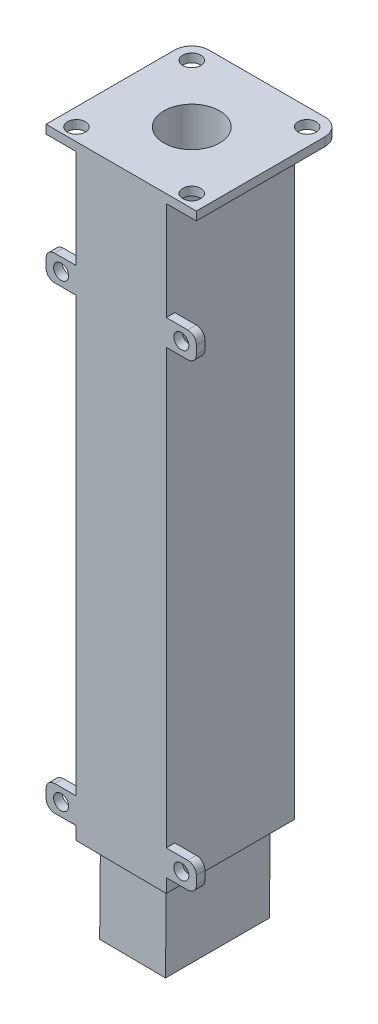
SolidWorks part; units mm, degrees
ref_plane "Plan de face" through (0, 0, 0) normal (0, 0, 1) x (1, 0, 0)
ref_plane "Plan de dessus" through (0, 0, 0) normal (0, 1, 0) x (1, 0, 0)
ref_plane "Plan de droite" through (0, 0, 0) normal (1, 0, 0) x (0, 0, -1)
sketch "Esquisse1" plane through (0, 0, 0) normal (0, 1, 0) x (1, 0, 0)
  line L0 (0, 0) -> (35, 0)
  line L1 (35, 0) -> (35, -35)
  line L2 (0, 0) -> (0, -35)
  line L3 (0, -35) -> (35, -35)
  dimension "D1" = 35
  dimension "D2" = 35
extrude "Boss.-Extru.1" add sketch "Esquisse1" along normal blind 2
sketch "Esquisse2" plane through (0, 2, 0) normal (0, 1, 0) x (1, 0, 0)
  line L0 (0, -33.935) -> (0, -35)
  line L1 (0, -33.935) -> (35, -33.935)
  line L6 (0, 0) -> (0, -35) construction
  line L7 (35, -35) -> (35, 0) construction
  line L8 (0, -35) -> (35, -35)
  line L9 (35, -35) -> (35, -33.935)
  circle A9 centre (30.935, -4.065) radius 1.75
  circle A10 centre (30.935, -30.935) radius 1.75
  circle A11 centre (4.065, -4.065) radius 1.75
  circle A12 centre (4.065, -30.935) radius 1.75
extrude "Enlèv. mat.-Extru.1" cut sketch "Esquisse2" against normal blind 2
sketch "Esquisse4" plane through (0, 2, 0) normal (0, 1, 0) x (1, 0, 0)
  line L0 (17.5, -33.935) -> (7, -33.935)
  line L1 (35, -33.935) -> (0, -33.935) construction
  line L2 (17.5, -33.935) -> (28, -33.935)
  line L3 (7, -4.065) -> (28, -4.065)
  line L4 (7, -33.935) -> (7, -4.065)
  line L5 (28, -4.065) -> (28, -33.935)
extrude "Boss.-Extru.2" add sketch "Esquisse4" along normal blind 280
sketch "Esquisse5" plane through (0, 0, 33.935) normal (0, 0, 1) x (1, 0, 0)
  line L0 (28, 251) -> (28, 257)
  line L1 (7, 282) -> (7, 2) construction
  line L2 (35, 251) -> (35, 257)
  line L3 (28, 282) -> (28, 2) construction
  line L4 (7, 31) -> (0, 31)
  line L5 (7, 25) -> (0, 25)
  line L6 (28, 25) -> (35, 25)
  line L7 (28, 282) -> (28, 257)
  line L8 (28, 257) -> (28, 25)
  line L10 (28, 251) -> (35, 251)
  line L11 (7, 251) -> (7, 257)
  line L12 (0, 31) -> (0, 25)
  line L13 (7, 31) -> (7, 25)
  line L14 (28, 31) -> (35, 31)
  line L15 (35, 31) -> (35, 25)
  line L16 (28, 31) -> (28, 25)
  line L17 (0, 251) -> (0, 257)
  line L18 (28, 257) -> (35, 257)
  line L19 (7, 257) -> (0, 257)
  line L20 (7, 251) -> (0, 251)
  circle A0 centre (3.5, 28) radius 1.75
  circle A1 centre (31.5, 28) radius 1.75
  circle A2 centre (31.5, 254) radius 1.75
  circle A3 centre (3.5, 254) radius 1.75
  line M4 (28, 2) -> (28, 282)
  line M6 (7, 282) -> (7, 2)
extrude "Boss.-Extru.3" add sketch "Esquisse5" against normal blind 2 contours L18 L10 L2 A2 M4 | L20 L19 L17 A3 M6 | L15 L14 L6 A1 M4 | L4 L12 L5 A0 M6
sketch "Esquisse6" plane through (0, 0, 33.935) normal (0, 0, 1) x (1, 0, 0)
  line L7 (0, 144) -> (0, 138)
  line L8 (0, 138) -> (7, 138)
  line L9 (7, 141) -> (7, 138)
  line L10 (7, 141) -> (7, 144)
  line L11 (0, 144) -> (7, 144)
  line L12 (0, 144) -> (0, 141)
  line L13 (0, 144) -> (7, 144)
  line L14 (28, 251) -> (28, 31) construction
  line L15 (28, 144) -> (28, 138)
  line L16 (28, 138) -> (35, 138)
  line L17 (35, 141) -> (35, 138)
  line L18 (35, 141) -> (35, 144)
  line L19 (28, 144) -> (35, 144)
  line L20 (28, 144) -> (28, 141)
  line L21 (0, 144) -> (0, 138)
  line L22 (0, 138) -> (7, 138)
  line L23 (7, 144) -> (7, 138)
  circle A1 centre (3.5, 141) radius 1.75
  circle A2 centre (31.5, 141) radius 1.75
  line M21 (28, 31) -> (28, 251)
  line M31 (7, 251) -> (7, 31)
extrude "Boss.-Extru.4" add sketch "Esquisse6" against normal blind 2 contours L11 L7 L8 A1 M31 | L19 L15 L16 L17 L18 A2 M21
sketch "Esquisse10" plane through (0, 282, 0) normal (0, 1, 0) x (1, 0, 0)
  line L0 (35, -33.935) -> (0, -33.935)
  line L1 (35, -33.935) -> (35, 0)
  line L2 (35, 0) -> (0, 0)
  line L3 (0, -33.935) -> (0, 0)
  circle A0 centre (30.935, -30.935) radius 1.75
  circle A1 centre (30.935, -4.065) radius 1.75
  circle A2 centre (4.065, -4.065) radius 1.75
  circle A3 centre (4.065, -30.935) radius 1.75
extrude "Boss.-Extru.5" add sketch "Esquisse10" against normal blind 2
sketch "Esquisse15" plane through (0, 282, 0) normal (0, 1, 0) x (1, 0, 0)
  circle A0 centre (17.5, -17.5) radius 6.5
  circle A1 centre (30.935, -4.065) radius 1.75
extrude "Enlèv. mat.-Extru.2" cut sketch "Esquisse15" against normal blind 373
fillet "Congé1" radius 2 12 edges at (35, 138, 32.935) (35, 144, 32.935) (35, 25, 32.935) (35, 31, 32.935) (0, 31, 32.935) (0, 25, 32.935) (0, 138, 32.935) (0, 144, 32.935) (0, 251, 32.935) (0, 257, 32.935) (35, 251, 32.935) (35, 257, 32.935)
fillet "Congé2" radius 4 4 edges at (0, 1, 0) (35, 1, 0) (0, 281, 0) (35, 281, 0)
sketch "Esquisse17" plane through (0, 0, 33.935) normal (0, 0, 1) x (1, 0, 0)
  line L0 (7, 144) -> (7, 138)
  line L1 (7, 138) -> (2, 138)
  line L2 (7, 144) -> (2, 144)
  line L3 (28, 144) -> (28, 138)
  line L4 (28, 138) -> (33, 138)
  line L5 (28, 144) -> (33, 144)
  line L6 (35, 142) -> (35, 140)
  line L7 (0, 142) -> (0, 140)
  line L8 (7, 150) -> (7, 144)
  line L9 (7, 144) -> (2, 144)
  line L10 (7, 150) -> (2, 150)
  line L11 (28, 150) -> (28, 144)
  line L12 (28, 144) -> (33, 144)
  line L13 (28, 150) -> (33, 150)
  line L14 (35, 148) -> (35, 146)
  line L15 (0, 148) -> (0, 146)
  line L16 (7, 138) -> (7, 132)
  line L17 (7, 132) -> (2, 132)
  line L18 (7, 138) -> (2, 138)
  line L19 (28, 138) -> (28, 132)
  line L20 (28, 132) -> (33, 132)
  line L21 (28, 138) -> (33, 138)
  line L22 (35, 136) -> (35, 134)
  line L23 (0, 136) -> (0, 134)
  arc A0 (0, 142) -> (2, 144) centre (2, 142) cw
  arc A2 (0, 140) -> (2, 138) centre (2, 140) ccw
  arc A3 (33, 144) -> (35, 142) centre (33, 142) cw
  arc A4 (35, 140) -> (33, 138) centre (33, 140) cw
  circle A5 centre (3.5, 141) radius 1.75
  circle A6 centre (31.5, 141) radius 1.75
  circle A7 centre (31.5, 141) radius 1.75
  arc A8 (0, 148) -> (2, 150) centre (2, 148) cw
  arc A9 (0, 146) -> (2, 144) centre (2, 146) ccw
  arc A10 (33, 150) -> (35, 148) centre (33, 148) cw
  arc A11 (35, 146) -> (33, 144) centre (33, 146) cw
  circle A12 centre (3.5, 147) radius 1.75
  circle A13 centre (31.5, 147) radius 1.75
  circle A14 centre (31.5, 147) radius 1.75
  arc A15 (0, 136) -> (2, 138) centre (2, 136) cw
  arc A16 (0, 134) -> (2, 132) centre (2, 134) ccw
  arc A17 (33, 138) -> (35, 136) centre (33, 136) cw
  arc A18 (35, 134) -> (33, 132) centre (33, 134) cw
  circle A19 centre (3.5, 135) radius 1.75
  circle A20 centre (31.5, 135) radius 1.75
  circle A21 centre (31.5, 135) radius 1.75
extrude "Boss.-Extru.6" add sketch "Esquisse17" against normal blind 2 contours L15 A9 L2 L8 L10 A8 A12 | L23 A16 L17 L16 L1 A15 A19 | A18 L22 A17 L4 L19 L20 A20 | A11 L14 A10 L13 L11 L5 A13
sketch "Esquisse18" plane through (0, 0, 33.935) normal (0, 0, 1) x (1, 0, 0)
  line L3 (2, 138) -> (7, 138)
  line L4 (7, 138) -> (7, 144)
  line L5 (2, 144) -> (7, 144)
  line L6 (37.3625, 138) -> (33, 138)
  line L9 (2, 144) -> (-2.3625, 144)
  line L10 (-2.3625, 144) -> (-2.3625, 138)
  line L11 (-2.3625, 138) -> (2, 138)
  line L12 (37.3625, 144) -> (37.3625, 138)
  line L13 (33, 144) -> (37.3625, 144)
  line L14 (33, 144) -> (28, 144)
  line L15 (28, 138) -> (28, 144)
  line L16 (33, 138) -> (28, 138)
extrude "Enlèv. mat.-Extru.3" cut sketch "Esquisse18" against normal blind 2
sketch "Esquisse19" plane through (0, 0, 33.935) normal (0, 0, 1) x (1, 0, 0)
  line L0 (7, 141) -> (140.1205, 139.7863)
  line L1 (7, 138) -> (7, 144) construction
  line L2 (140.1205, 139.7863) -> (140.1205, -30.3803)
  line L3 (140.1205, -30.3803) -> (-166.1504, -30.3803)
  line L4 (-166.1504, -30.3803) -> (-166.1504, 141)
  line L5 (-166.1504, 141) -> (7, 141)
extrude "Enlèv. mat.-Extru.4" cut sketch "Esquisse19" against normal blind 307 and the other way blind 128 contours L5 L0 L2 L3 L4
sketch "Esquisse20" plane through (1.286, 141.0521, 0) normal (-0.0091, -1, 0) x (1, -0.0091, 0)
  line L5 (8.5427, 31.1066) -> (23.8867, 31.1066)
  line L6 (8.5427, 31.1066) -> (8.5427, 6.8934)
  line L7 (8.5427, 6.8934) -> (23.8867, 6.8934)
  line L8 (23.8867, 31.1066) -> (23.8867, 6.8934)
  circle A0 centre (16.2147, 17.5) radius 6.5
extrude "Boss.-Extru.7" add sketch "Esquisse20" along normal blind 20
sketch "Esquisse21" plane through (0, 280, 0) normal (0, -1, 0) x (1, 0, 0)
  circle A0 centre (4.065, 4.065) radius 2.1
  circle A1 centre (30.935, 4.065) radius 2.1
  circle A2 centre (30.935, 30.935) radius 2.1
  circle A3 centre (4.065, 30.935) radius 2.1
extrude "Enlèv. mat.-Extru.5" cut sketch "Esquisse21" against normal blind 10 contours A1 | A0 | A3 | A2
